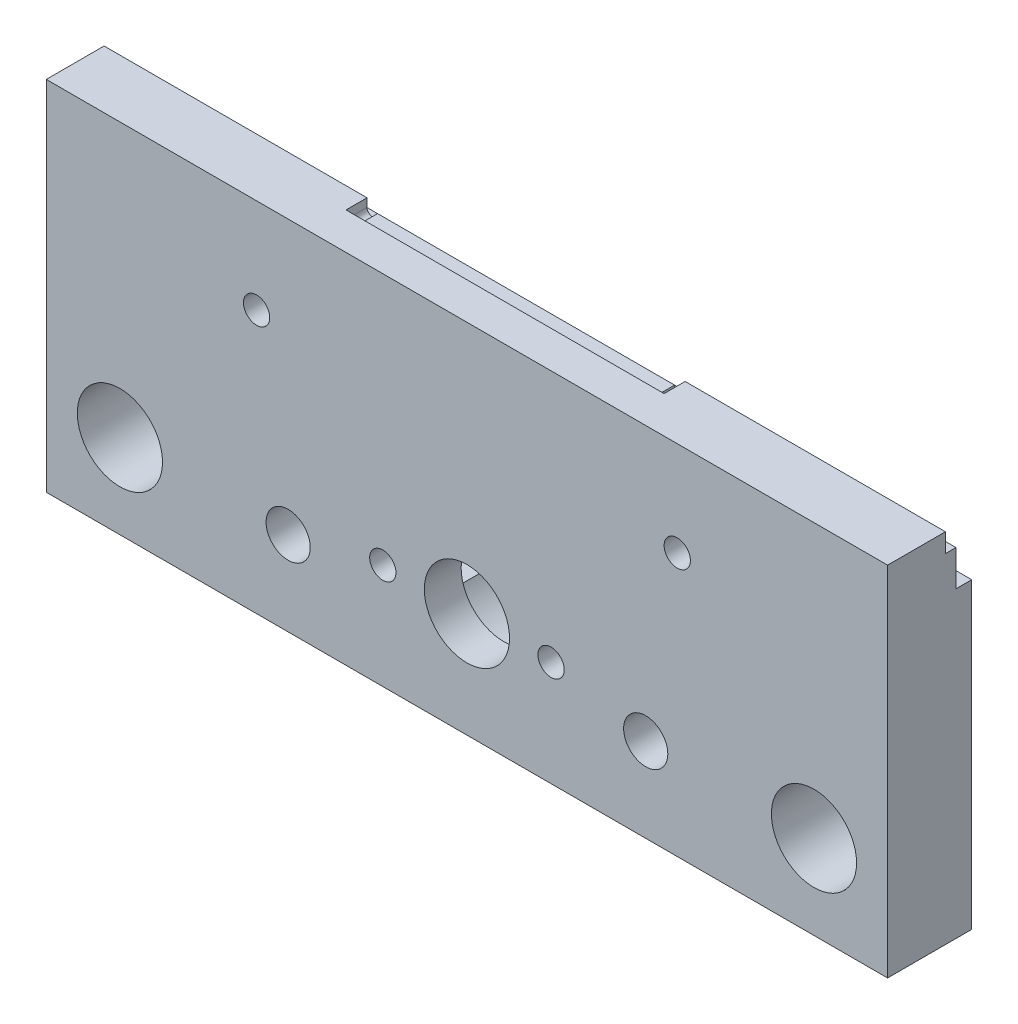
SolidWorks part; units mm, degrees
ref_plane "前视基准面" through (0, 0, 0) normal (0, 0, 1) x (1, 0, 0)
ref_plane "上视基准面" through (0, 0, 0) normal (0, 1, 0) x (1, 0, 0)
ref_plane "右视基准面" through (0, 0, 0) normal (1, 0, 0) x (0, 0, -1)
sketch "前视图草图" plane through (0, 0, 0) normal (0, 0, 1) x (1, 0, 0)
  line L0 (0, 0) -> (44.4821, 0) construction
  line L1 (0, 0) -> (0, 28.3185) construction
sketch "草图2" plane through (0, 0, 0) normal (0, 0, 1) x (1, 0, 0)
  line L0 (0, 0) -> (80, 0)
  line L1 (-200000, 0) -> (200044.4821, 0) construction
  line L2 (80, 0) -> (80, 34)
  line L3 (80, 34) -> (0, 34)
  line L4 (0, -200000) -> (0, 200028.3185) construction
  line L5 (0, 34) -> (0, 0)
  circle A0 centre (7, 8) radius 4.05
  circle A1 centre (40, 10) radius 4.05
  circle A2 centre (73, 8) radius 4.05
  dimension "D3" = 8
  dimension "D5" = 10
  dimension "D9" = 8.1
  dimension "D10" = 8.1
  dimension "D11" = 8.1
  dimension "D1" = 34
  dimension "D2" = 80
  dimension "D4" = 7
  dimension "D6" = 7
  dimension "D7" = 8
  dimension "D8" = 40
extrude "凸台-拉伸1" add sketch "草图2" along normal blind 8
sketch "草图3" plane through (0, 0, 8) normal (0, 0, 1) x (1, 0, 0)
  line L0 (16.088, 8) -> (31.4805, 8) construction
  line L1 (7, 8) -> (7, 16.8386) construction
  line L2 (73, 8) -> (73, 16.5917) construction
  line L4 (-200000, 0) -> (200044.4821, 0) construction
  circle A2 centre (23, 8) radius 2.55
  circle A3 centre (57, 8) radius 2.55
  dimension "D4" = 5.1
  dimension "D5" = 5.1
  dimension "D1" = 8
  dimension "D2" = 16
  dimension "D3" = 16
sketch "草图4" plane through (80, 0, 0) normal (1, 0, 0) x (0, 0, -1)
  line L1 (0, -200000) -> (0, 200028.3185) construction
  line L2 (-1.5, 32.2) -> (-2.5, 32.2)
  line L3 (-2.5, 32.2) -> (-2.5, 34)
  line L4 (-8, 34) -> (0, 34) construction
  line L5 (-2.5, 34) -> (0, 34)
  line L6 (-1.5, 32.2) -> (-1.5, 28.8)
  line L7 (-1.5, 28.8) -> (0, 28.8)
  line L8 (0, 28.8) -> (0, 34)
  dimension "D1" = 3.4
  dimension "D2" = 2.5
  dimension "D3" = 1.5
  dimension "D4" = 1.8
extrude "切除-拉伸2" cut sketch "草图4" against normal through all
sketch "草图5" plane through (0, 0, 8) normal (0, 0, 1) x (1, 0, 0)
  line L0 (40, 10) -> (56.5376, 10) construction
  circle A0 centre (40, 10) radius 8 construction
  circle A1 centre (48, 10) radius 1.55
  circle A2 centre (32, 10) radius 1.55
  dimension "D1" = 3.1
  dimension "D2" = 3.1
  dimension "D3" = 16
sketch "草图8" plane through (0, 0, 0) normal (0, 0, -1) x (-1, 0, 0)
  line L0 (-40, 10) -> (-57.3165, 10) construction
  line L1 (-40, 20) -> (-40, 35.6562) construction
  line L2 (-30.5, 12.85) -> (-49.5, 12.85)
  line L3 (-49.5, 7.15) -> (-30.5, 7.15)
  line L4 (200000, 0) -> (-200044.4821, 0) construction
  arc A0 (-30.5, 7.15) -> (-30.5, 12.85) centre (-30.5, 10) ccw
  arc A1 (-49.5, 12.85) -> (-49.5, 7.15) centre (-49.5, 10) ccw
  dimension "D1" = 5.7
  dimension "D2" = 9.5
  dimension "D3" = 9.5
  dimension "D4" = 10
sketch "草图11" plane through (0, 0, 0) normal (0, 0, -1) x (-1, 0, 0)
  line L0 (-40, 20) -> (-58.6363, 20) construction
  line L1 (-80, 0) -> (-80, 28.8) construction
  line L2 (0, -200000) -> (0, 200028.3185) construction
  line L3 (-40, 20) -> (-40, 13.5744) construction
  line L4 (-28.772, 25) -> (-45.9396, 25) construction
  line L5 (0, 34) -> (-80, 34) construction
  circle A0 centre (-60, 25) radius 1.55
  circle A1 centre (-20, 25) radius 1.55
  point P23 (-40, 20)
  dimension "D1" = 3.1
  dimension "D2" = 3.1
  dimension "D3" = 20
  dimension "D4" = 20
  dimension "D5" = 9
extrude "切除-拉伸12" cut sketch "草图8" against normal blind 4.5
sketch "草图20" plane through (0, 0, 0) normal (0, 0, -1) x (-1, 0, 0)
  circle A0 centre (-40, 10) radius 6.25
  dimension "D1" = 12.5
extrude "切除-拉伸13" cut sketch "草图20" against normal blind 4.5
sketch "草图12" plane through (0, 0, 0) normal (0, 0, -1) x (-1, 0, 0)
  line L0 (-62.5, 22.15) -> (-57.5, 22.15)
  line L1 (-57.5, 27.85) -> (-62.5, 27.85)
  line L4 (0, 34) -> (-80, 34) construction
  line L5 (-39.1423, 25) -> (-43.2672, 25) construction
  line L6 (-60, 21) -> (-60, 25.2385) construction
  line L7 (-20, 21) -> (-20, 26.1603) construction
  line L8 (-40, 20) -> (-40, 24.3689) construction
  line L9 (-17.5, 27.85) -> (-22.5, 27.85)
  line L10 (-22.5, 22.15) -> (-17.5, 22.15)
  line L11 (-40, -199980) -> (-40, 200035.6562) construction
  line L12 (199971.228, 25) -> (-200045.9396, 25) construction
  line L13 (-80, 0) -> (-80, 28.8) construction
  line L14 (0, -200000) -> (0, 200028.3185) construction
  arc A0 (-62.5, 27.85) -> (-62.5, 22.15) centre (-62.5, 25) ccw
  arc A1 (-57.5, 22.15) -> (-57.5, 27.85) centre (-57.5, 25) ccw
  arc A4 (-17.5, 22.15) -> (-17.5, 27.85) centre (-17.5, 25) ccw
  arc A5 (-22.5, 27.85) -> (-22.5, 22.15) centre (-22.5, 25) ccw
  point P16 (-38, 21)
  point P28 (-40, 25)
  dimension "D2" = 9
  dimension "D3" = 5
  dimension "D4" = 2.5
  dimension "D5" = 20
  dimension "D6" = 20
  dimension "D1" = 2
sketch "草图19" plane through (0, 0, 2.5) normal (0, 0, -1) x (-1, 0, 0)
  line L0 (0, 34) -> (-80, 34) construction
  line L1 (-25, 34) -> (-55.2479, 34)
  line L2 (-25, 34) -> (-25, 33.2)
  line L3 (-26, 33.2) -> (-54.2479, 33.2)
  line L4 (-55.2479, 34) -> (-55.2479, 33.2)
  line L5 (0, -200000) -> (0, 200028.3185) construction
  line L7 (0, 32.2) -> (-80, 32.2) construction
  line L8 (-56.3335, 32.7) -> (-52.9089, 32.7) construction
  line L9 (-55.2479, 1028.5823) -> (-55.2479, 33.2) construction
  line L10 (-25, 1028.5823) -> (-25, 32.7) construction
  line L11 (-55.2479, 32.7) -> (-55.2479, -973.3) construction
  line L12 (-25, 32.7) -> (-25, -973.3) construction
  arc A3 (-55.2479, 33.2) -> (-54.2479, 33.2) centre (-54.7479, 33.2) ccw
  arc A6 (-26, 33.2) -> (-25, 33.2) centre (-25.5, 33.2) ccw
  dimension "D3" = 1
  dimension "D4" = 1
  dimension "D2" = 0.8
  dimension "D1" = 0.5
  dimension "D9" = 25
extrude "切除-拉伸11" cut sketch "草图19" against normal blind 2
hole_wizard "M3 螺纹孔7" positions "草图23" profile "草图24" tap size "M3" standard "GB" end condition through all
sketch "草图23" plane through (0, 0, 8) normal (0, 0, 1) x (1, 0, 0)
  point P0 (20, 25)
  point P3 (60, 25)
  point P6 (32, 10)
  point P9 (48, 10)
sketch "草图24" plane through (20, 25, 8) normal (1, 0, 0) x (0, -1, 0)
  line L0 (0, 0) -> (0, 8)
  line L1 (0, 8) -> (1.25, 8)
  line L2 (1.25, 8) -> (1.25, 0)
  line L5 (1.25, 0) -> (0, 0)
  line L11 (0, -6.35) -> (0, 107.95) construction
  dimension "通孔螺纹孔钻头直径" = 2.5
  dimension "通孔螺纹孔钻头深度" = 8
cosmetic thread "孔螺蚊线1" parameters "D2"=3
cosmetic thread "孔螺蚊线2" parameters "D2"=3
cosmetic thread "孔螺蚊线3" parameters "D2"=3
cosmetic thread "孔螺蚊线4" parameters "D2"=3
hole_wizard "M5 螺纹孔1" positions "草图25" profile "草图26" tap size "M5" standard "GB" end condition through all
sketch "草图25" plane through (0, 0, 8) normal (0, 0, 1) x (1, 0, 0)
  point P0 (23, 8)
  point P3 (57, 8)
sketch "草图26" plane through (23, 8, 8) normal (1, 0, 0) x (0, -1, 0)
  line L0 (0, 0) -> (0, 8)
  line L1 (0, 8) -> (2.1, 8)
  line L2 (2.1, 8) -> (2.1, 0)
  line L5 (2.1, 0) -> (0, 0)
  line L11 (0, -6.35) -> (0, 107.95) construction
  dimension "通孔螺纹孔钻头直径" = 4.2
  dimension "通孔螺纹孔钻头深度" = 8
cosmetic thread "孔螺蚊线5" parameters "D2"=5
cosmetic thread "孔螺蚊线6" parameters "D2"=5
